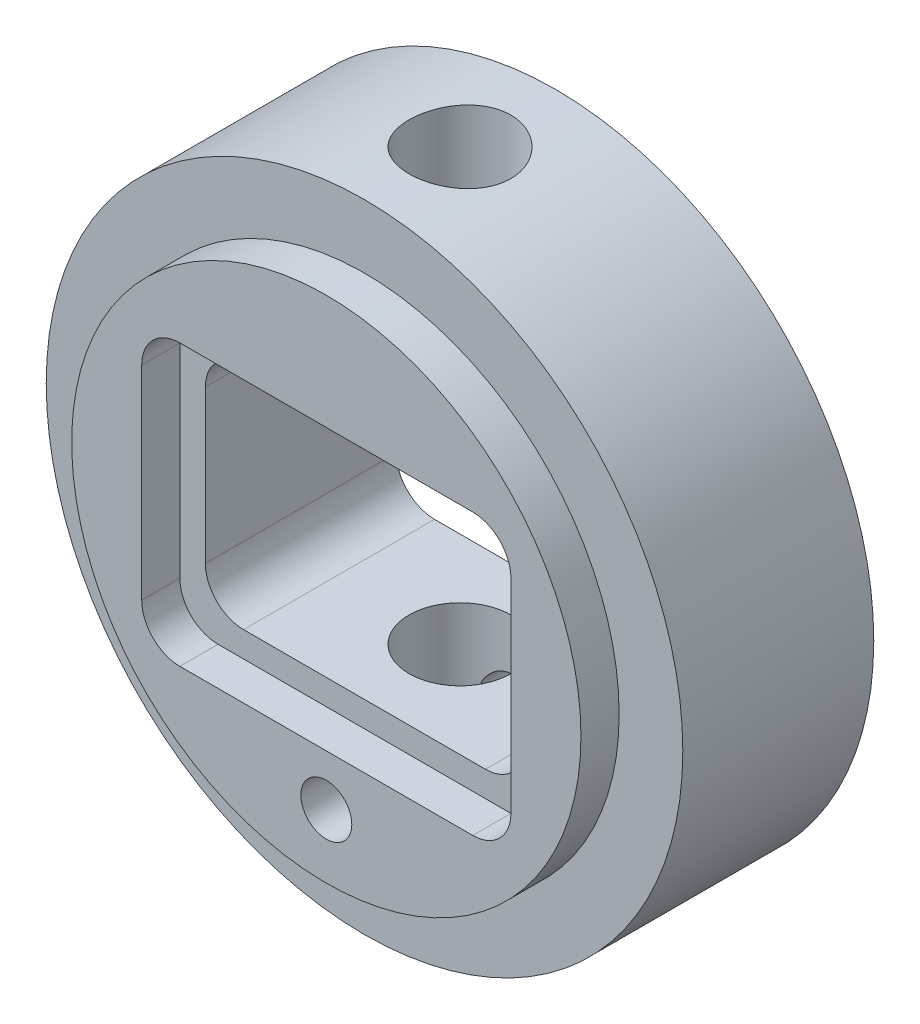
SolidWorks part; units mm, degrees
ref_plane "Front Plane" through (0, 0, 0) normal (0, 0, 1) x (1, 0, 0)
ref_plane "Top Plane" through (0, 0, 0) normal (0, 1, 0) x (1, 0, 0)
ref_plane "Right Plane" through (0, 0, 0) normal (1, 0, 0) x (0, 0, -1)
sketch "Sketch1" plane through (0, 0, 0) normal (0, 0, 1) x (1, 0, 0)
  line L1 (12.5, -9) -> (-12.5, -9)
  line L2 (12.5, -9) -> (12.5, 9)
  line L3 (12.5, 9) -> (-12.5, 9)
  line L4 (-12.5, -9) -> (-12.5, 9)
  line L5 (12.5, -9) -> (-12.5, 9) construction
  line L6 (12.5, 9) -> (-12.5, -9) construction
  circle A0 centre (0, 0) radius 25
  dimension "D1" = 50
  dimension "D2" = 25
  dimension "D3" = 18
extrude "Boss-Extrude1" add sketch "Sketch1" along normal blind 15
sketch "Sketch2" plane through (0, 0, 15) normal (0, 0, 1) x (1, 0, 0)
  line L0 (12.5, 9) -> (-12.5, 9) construction
  line L1 (-14.5, -11) -> (14.5, -11)
  line L2 (-14.5, -11) -> (-14.5, 11)
  line L3 (-14.5, 11) -> (14.5, 11)
  line L4 (14.5, -11) -> (14.5, 11)
  line L5 (-14.5, -11) -> (14.5, 11) construction
  line L6 (-14.5, 11) -> (14.5, -11) construction
  line L7 (12.5, -9) -> (12.5, 9) construction
  circle A0 centre (0, 0) radius 20
  dimension "D1" = 40
  dimension "D2" = 2
  dimension "D3" = 2
extrude "Boss-Extrude2" add sketch "Sketch2" along normal blind 3
hole_wizard "Ø4.0mm Dowel Hole1" positions "Sketch3" profile "Sketch4" hole size "Ø4.0" standard "ANSI Metric" end condition through all
sketch "Sketch3" plane through (0, 0, 18) normal (0, 0, 1) x (1, 0, 0)
  point P0 (0, -15)
  point P4 (0, 0)
  dimension "D1" = 15
sketch "Sketch4" plane through (0, -15, 18) normal (1, 0, 0) x (0, -1, 0)
  line L0 (0, 0) -> (0, 18)
  line L1 (0, 18) -> (2, 18)
  line L2 (2, 18) -> (2, 0)
  line L5 (2, 0) -> (0, 0)
  line L11 (0, -6.35) -> (0, 107.95) construction
  dimension "Thru Hole Dia." = 4
  dimension "Thru Hole Depth" = 18
hole_wizard "Ø8.0mm Dowel Hole1" positions "Sketch5" profile "Sketch6" hole size "Ø8.0" standard "ANSI Metric"
sketch "Sketch5" plane through (0, 9, 0) normal (0, -1, 0) x (-1, 0, 0)
  line L0 (-12.5, -7.5) -> (8.5569, -7.5) construction
  line L1 (-12.5, -15) -> (-12.5, 0) construction
  line L3 (0, -15) -> (0, -3.1407) construction
  line L4 (-12.5, -15) -> (12.5, -15) construction
  point P0 (0, -7.5)
  point P16 (0, 0)
sketch "Sketch6" plane through (0, 9, 7.5) normal (1, 0, 0) x (0, 0, -1)
  line L0 (0, 0) -> (0, 16)
  line L1 (0, 16) -> (4, 16)
  line L2 (4, 16) -> (4, 0)
  line L5 (4, 0) -> (0, 0)
  line L11 (0, -6.35) -> (0, 107.95) construction
  dimension "Thru Hole Dia." = 8
  dimension "Thru Hole Depth" = 16
hole_wizard "Ø8.0mm Dowel Hole2" positions "Sketch7" profile "Sketch8" hole size "Ø8.0" standard "ANSI Metric" end condition through all
sketch "Sketch7" plane through (0, -9, 0) normal (0, 1, 0) x (1, 0, 0)
  line L0 (-8.5569, -7.5) -> (12.5, -7.5) construction
  line L3 (0, -15) -> (0, -2.6195) construction
  line L5 (-12.5, -15) -> (12.5, -15) construction
  line L6 (12.5, -15) -> (12.5, 0) construction
  point P0 (0, -7.5)
  point P16 (3.1567, 0.5212)
  point P17 (0, 0)
  point P20 (0, -15)
  point P21 (0, 0)
  point P24 (12.5, -7.5)
sketch "Sketch8" plane through (0, -9, 7.5) normal (1, 0, 0) x (0, 0, 1)
  line L0 (0, 0) -> (0, 16)
  line L1 (0, 16) -> (4, 16)
  line L2 (4, 16) -> (4, 0)
  line L5 (4, 0) -> (0, 0)
  line L11 (0, -6.35) -> (0, 107.95) construction
  dimension "Thru Hole Dia." = 8
  dimension "Thru Hole Depth" = 16
fillet "Fillet1" radius 3 8 edges at (-14.5, 11, 16.5) (-14.5, -11, 16.5) (14.5, 11, 16.5) (14.5, -11, 16.5) (12.5, -9, 7.5) (12.5, 9, 7.5) (-12.5, -9, 7.5) (-12.5, 9, 7.5)
